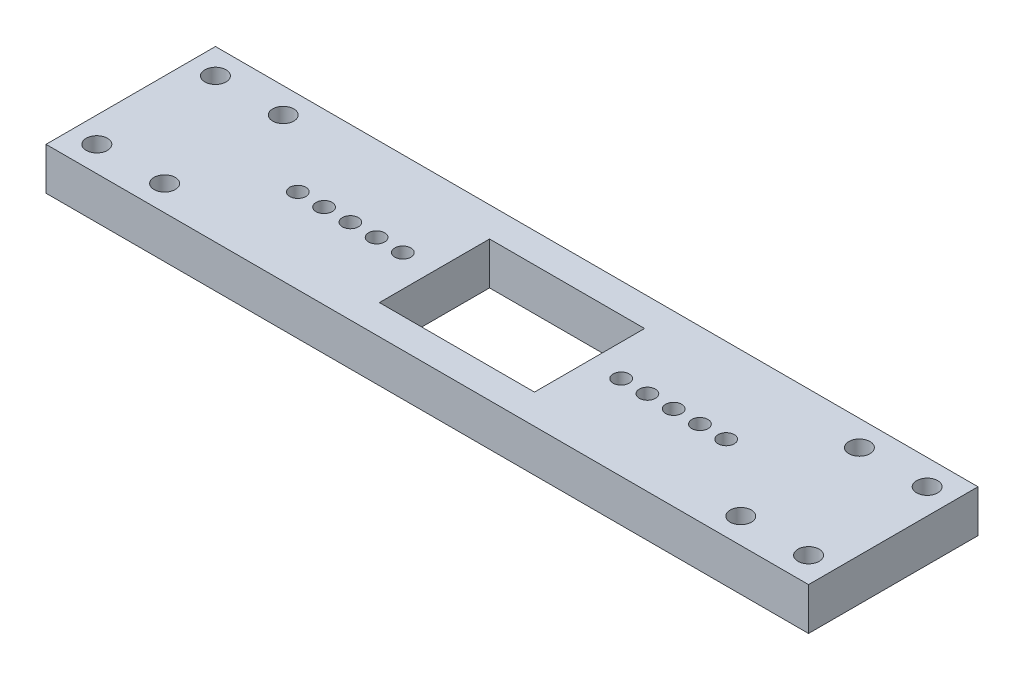
SolidWorks part; units mm, degrees
ref_plane "Front Plane" through (0, 0, 0) normal (0, 0, 1) x (1, 0, 0)
ref_plane "Top Plane" through (0, 0, 0) normal (0, 1, 0) x (1, 0, 0)
ref_plane "Right Plane" through (0, 0, 0) normal (1, 0, 0) x (0, 0, -1)
sketch "Sketch1" plane through (0, 0, 0) normal (0, 1, 0) x (1, 0, 0)
  line L0 (45, 20) -> (45, 0) construction
  line L1 (0, 0) -> (90, 0)
  line L2 (0, 0) -> (0, 20)
  line L3 (0, 20) -> (90, 20)
  line L4 (90, 0) -> (90, 20)
  line L5 (0, 10) -> (90, 10) construction
  line L6 (54.15, 16.5) -> (35.85, 16.5)
  line L7 (54.15, 16.5) -> (54.15, 3.5)
  line L8 (54.15, 3.5) -> (35.85, 3.5)
  line L9 (35.85, 16.5) -> (35.85, 3.5)
  circle A0 centre (57.88, 10) radius 0.95
  circle A5 centre (60.98, 10) radius 0.95
  circle A6 centre (64.08, 10) radius 0.95
  circle A7 centre (67.18, 10) radius 0.95
  circle A8 centre (70.28, 10) radius 0.95
  circle A9 centre (19.72, 10) radius 0.95
  circle A10 centre (22.82, 10) radius 0.95
  circle A11 centre (25.92, 10) radius 0.95
  circle A12 centre (29.02, 10) radius 0.95
  circle A13 centre (32.12, 10) radius 0.95
  point P11 (45, 16.5)
  point P12 (45, 3.5)
  point P15 (35.85, 10)
  point P16 (54.15, 10)
  dimension "D6" = 1.9
  dimension "D1" = 90
  dimension "D2" = 20
  dimension "D3" = 45
  dimension "D4" = 18.3
  dimension "D5" = 13
  dimension "D7" = 12.88
  dimension "D8" = 5
extrude "Boss-Extrude1" add sketch "Sketch1" along normal blind 5
ref_plane "Plane1" through (0, 0, -10) normal (0, 0, 1) x (1, 0, 0)
ref_plane "Plane2" through (45, 0, 0) normal (1, 0, 0) x (0, 0, -1)
sketch "Sketch3" plane through (0, 5, 0) normal (0, 1, 0) x (1, 0, 0)
  line L0 (0, 0) -> (90, 0) construction
  line L1 (90, 0) -> (90, 20) construction
  line L2 (-2.75, 10) -> (2.75, 10) construction
  line L3 (45, -2.75) -> (45, 2.75) construction
  circle A0 centre (87, 3) radius 1.25
  circle A1 centre (79, 3) radius 1.25
  circle A2 centre (79, 17) radius 1.25
  circle A3 centre (87, 17) radius 1.25
  circle A4 centre (3, 17) radius 1.25
  circle A5 centre (11, 17) radius 1.25
  circle A6 centre (11, 3) radius 1.25
  circle A7 centre (3, 3) radius 1.25
  dimension "D1" = 2.5
  dimension "D2" = 3
  dimension "D4" = 8
  dimension "D3" = 3
extrude "Cut-Extrude1" cut sketch "Sketch3" against normal up to next
